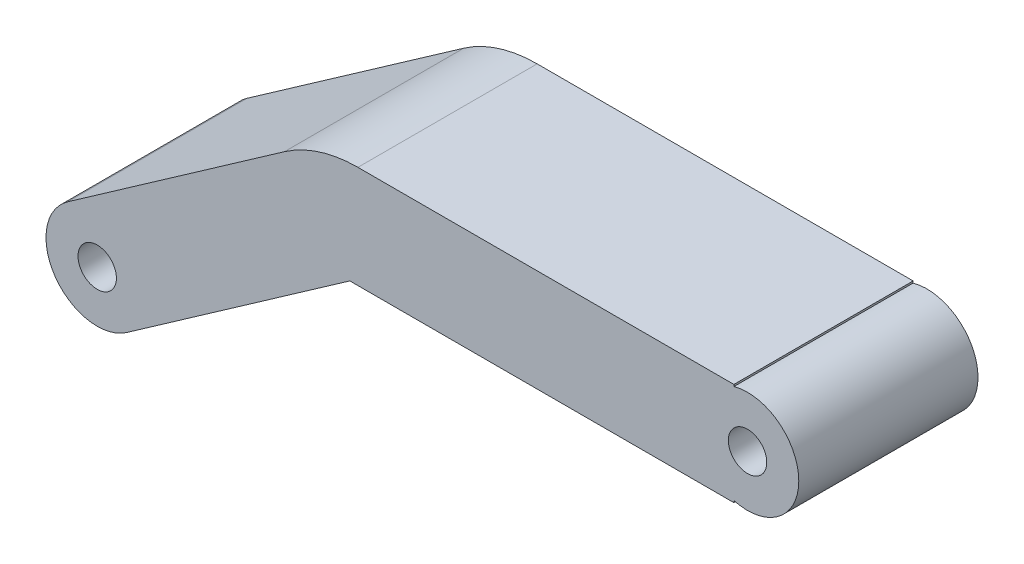
SolidWorks part; units mm, degrees
ref_plane "前视基准面" through (0, 0, 0) normal (0, 0, 1) x (1, 0, 0)
ref_plane "上视基准面" through (0, 0, 0) normal (0, 1, 0) x (1, 0, 0)
ref_plane "右视基准面" through (0, 0, 0) normal (1, 0, 0) x (0, 0, -1)
sketch "草图1" plane through (0, 0, 0) normal (0, 0, 1) x (1, 0, 0)
  line L0 (15.6052, 4.0165) -> (15.6052, 4.1614)
  line L1 (15.6052, -3.8386) -> (-14.3948, -3.8386)
  line L2 (15.6052, -3.8386) -> (15.6052, -3.6938)
  line L3 (15.6052, 4.1614) -> (-16.9172, 4.1614)
  line L7 (-14.3948, -3.8386) -> (-31.8334, -16.0492)
  line L8 (-36.422, -9.496) -> (-16.9172, 4.1614)
  line L9 (-34.1277, -1012.7726) -> (-34.1277, 48987.2274) construction
  line L10 (16.6718, -999.8386) -> (16.6718, 49000.1614) construction
  arc A0 (15.6052, -3.6938) -> (15.6052, 4.0165) centre (16.6718, 0.1614) ccw
  arc A1 (-36.422, -9.496) -> (-31.8334, -16.0492) centre (-34.1277, -12.7726) ccw
  circle A2 centre (-34.1277, -12.7726) radius 1.5
  circle A3 centre (16.6718, 0.1614) radius 1.5
  point P0 (0, 0)
  dimension "D3" = 8
  dimension "D6" = 8
  dimension "D7" = 3
  dimension "D8" = 3
  dimension "D1" = 8
  dimension "D2" = 30
  dimension "D4" = 145
  dimension "D5" = 8
  dimension "D9" = 50.7995
extrude "凸台-拉伸2" add sketch "草图1" along normal blind 14
fillet "圆角1" radius 10 1 edges at (-16.9172, 4.1614, 7)
